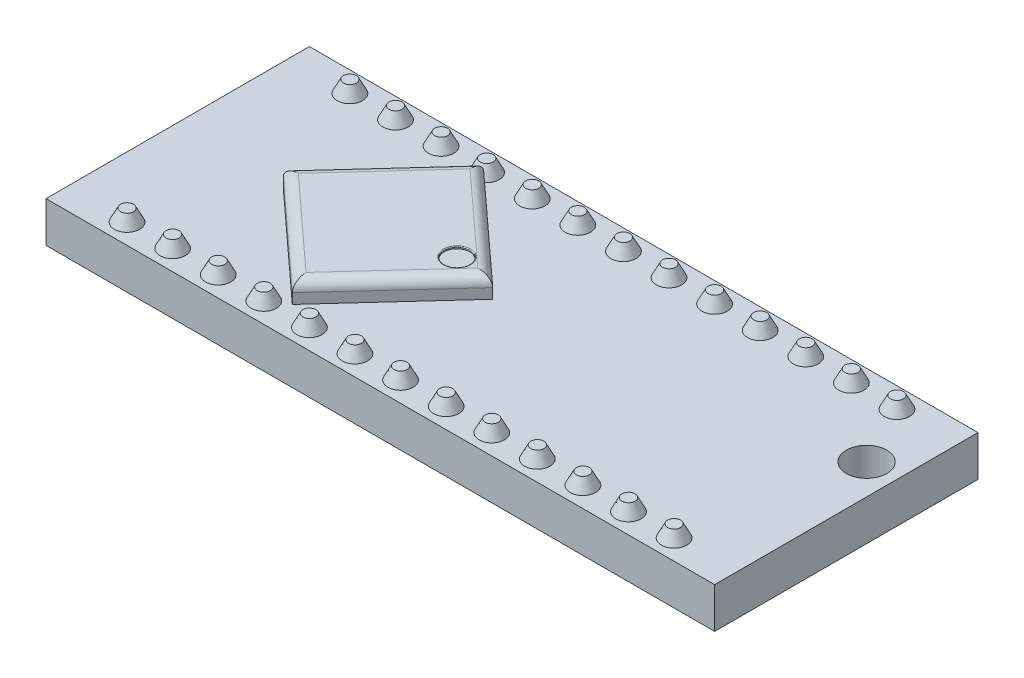
SolidWorks part; units mm, degrees
ref_plane "Front Plane" through (0, 0, 0) normal (0, 0, 1) x (1, 0, 0)
ref_plane "Top Plane" through (0, 0, 0) normal (0, 1, 0) x (1, 0, 0)
ref_plane "Right Plane" through (0, 0, 0) normal (1, 0, 0) x (0, 0, -1)
sketch "Sketch1" plane through (0, 0, 0) normal (0, 1, 0) x (1, 0, 0)
  line L1 (-16.5, 6.5) -> (16.5, 6.5)
  line L2 (-16.5, 6.5) -> (-16.5, -6.5)
  line L3 (-16.5, -6.5) -> (16.5, -6.5)
  line L4 (16.5, 6.5) -> (16.5, -6.5)
  line L5 (-16.5, 6.5) -> (16.5, -6.5) construction
  line L6 (-16.5, -6.5) -> (16.5, 6.5) construction
  point P0 (0, 0)
  dimension "D1" = 13
  dimension "D2" = 33
extrude "Boss-Extrude1" add sketch "Sketch1" along normal blind 2
sketch "Sketch2" plane through (0, 2, 0) normal (0, 1, 0) x (1, 0, 0)
  line L0 (-11.0637, -0.2218) -> (-5.8971, -4.9448)
  line L1 (-11.0637, -0.2218) -> (-6.3407, 4.9448)
  line L2 (-5.8971, -4.9448) -> (-1.1741, 0.2218)
  line L3 (-6.3407, 4.9448) -> (-1.1741, 0.2218)
  line L4 (-11.0637, -0.2218) -> (-1.1741, 0.2218) construction
  line L5 (-5.8971, -4.9448) -> (-6.3407, 4.9448) construction
  point P1 (-6.1189, 0)
  dimension "D1" = 7
  dimension "D2" = 7
extrude "Boss-Extrude2" add sketch "Sketch2" along normal blind 1
fillet "Fillet1" radius 0.5 4 edges at (-3.7574, 3, -2.5833) (-3.5356, 3, 2.3615) (-8.4804, 3, 2.5833) (-8.7022, 3, -2.3615)
sketch "Sketch3" plane through (0, 3, 0) normal (0, 1, 0) x (1, 0, 0)
  circle A0 centre (-2.8689, 0.1515) radius 0.6312
extrude "Cut-Extrude1" cut sketch "Sketch3" against normal blind 0.1
fillet "Fillet2" radius 0.04 1 edges at (-2.8689, 3, 0.4797)
sketch "Sketch4" plane through (0, 2, 0) normal (0, 1, 0) x (1, 0, 0)
  line L0 (16.5, 6.5) -> (-16.5, 6.5) construction
  line L1 (-16.5, 6.5) -> (-16.5, -6.5) construction
  line L3 (-55, 0) -> (55, 0) construction
  circle A0 centre (-13.5, 5.5) radius 0.625
  circle A1 centre (-11.25, 5.5) radius 0.625
  circle A2 centre (-9, 5.5) radius 0.625
  circle A3 centre (-6.75, 5.5) radius 0.625
  circle A4 centre (-4.5, 5.5) radius 0.625
  circle A5 centre (-2.25, 5.5) radius 0.625
  circle A6 centre (0, 5.5) radius 0.625
  circle A7 centre (2.25, 5.5) radius 0.625
  circle A8 centre (4.5, 5.5) radius 0.625
  circle A9 centre (6.75, 5.5) radius 0.625
  circle A10 centre (9, 5.5) radius 0.625
  circle A11 centre (11.25, 5.5) radius 0.625
  circle A12 centre (13.5, 5.5) radius 0.625
  circle A13 centre (-13.5, -5.5) radius 0.625
  circle A14 centre (-11.25, -5.5) radius 0.625
  circle A15 centre (-9, -5.5) radius 0.625
  circle A16 centre (-6.75, -5.5) radius 0.625
  circle A17 centre (-4.5, -5.5) radius 0.625
  circle A18 centre (-2.25, -5.5) radius 0.625
  circle A19 centre (0, -5.5) radius 0.625
  circle A20 centre (2.25, -5.5) radius 0.625
  circle A21 centre (4.5, -5.5) radius 0.625
  circle A22 centre (6.75, -5.5) radius 0.625
  circle A23 centre (9, -5.5) radius 0.625
  circle A24 centre (11.25, -5.5) radius 0.625
  circle A25 centre (13.5, -5.5) radius 0.625
  dimension "D1" = 1
  dimension "D3" = 1.25
  dimension "D2" = 3
  dimension "D4" = 13
  dimension "D5" = 13
extrude "Boss-Extrude3" add sketch "Sketch4" along normal blind 0.6 draft 27 contours A0 | A1 | A2 | A3 | A4 | A5 | A6 | A7 | A8 | A9 | A10 | A11 | A12 | A25 | A24 | A23 | A22 | A21 | A20 | A19 | A18 | A17 | A16 | A15 | A13 | A14
sketch "Sketch7" plane through (0, 2, 0) normal (0, 1, 0) x (1, 0, 0)
  line L0 (16.5, -6.5) -> (16.5, 6.5) construction
  line L2 (16.5, 6.5) -> (-16.5, 6.5) construction
  circle A0 centre (15, 2.5) radius 1
  dimension "D1" = 2
  dimension "D2" = 1.5
  dimension "D3" = 4
extrude "Cut-Extrude2" cut sketch "Sketch7" against normal blind 3
